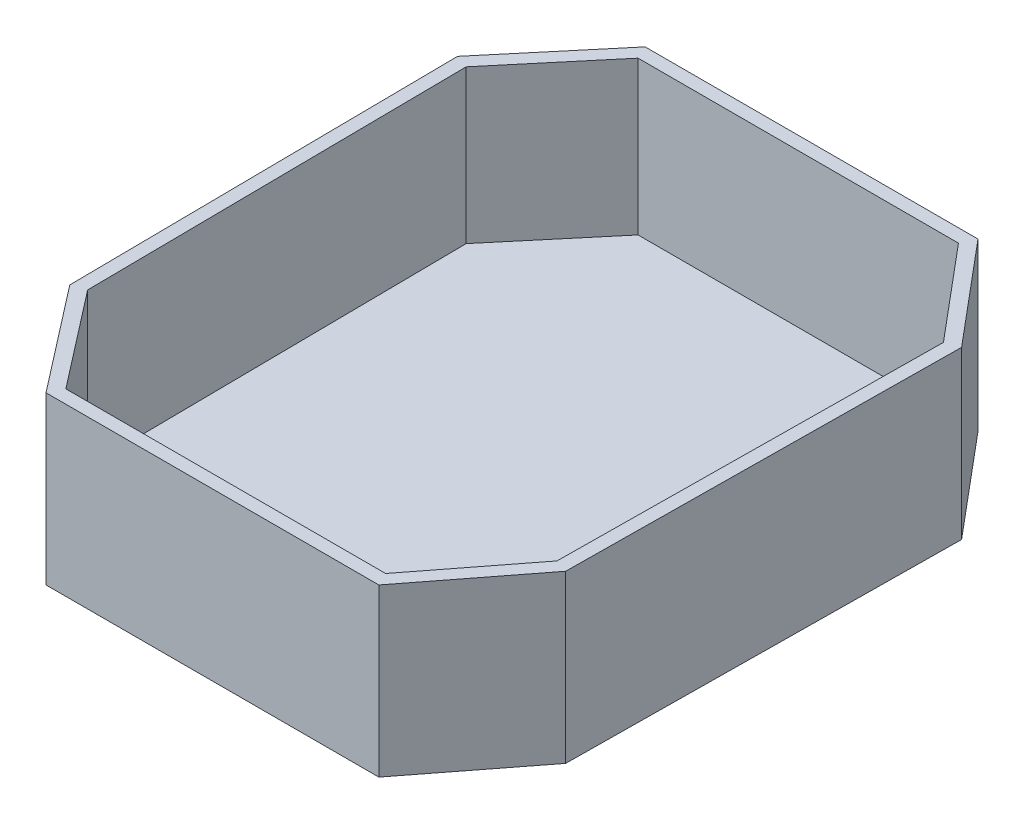
SolidWorks part; units mm, degrees
ref_plane "Ebene vorne" through (0, 0, 0) normal (0, 0, 1) x (1, 0, 0)
ref_plane "Ebene oben" through (0, 0, 0) normal (0, 1, 0) x (1, 0, 0)
ref_plane "Ebene rechts" through (0, 0, 0) normal (1, 0, 0) x (0, 0, -1)
sketch "Skizze1" plane through (0, 0, 0) normal (0, 1, 0) x (1, 0, 0)
  line L0 (-71.7828, 0) -> (65.2574, 0) construction
  line L1 (-55, 0) -> (55, 0) construction
  line L2 (0, 50.8602) -> (0, -44.8504) construction
  line L3 (0, -55) -> (0, 55) construction
  line L4 (0, -50.1714) -> (-25, -50.1714)
  line L5 (-25, -50.1714) -> (-37.2443, -34.3575)
  line L6 (-37.2443, -34.3575) -> (-37.8558, 24.5078)
  line L7 (-37.8558, 24.5078) -> (-25, 39.8286)
  line L8 (-25, 39.8286) -> (0, 39.8286)
  line L9 (0, 39.8286) -> (0, -50.1714)
  dimension "D1" = 25
  dimension "D2" = 130
  dimension "D3" = 20
  dimension "D4" = 90
extrude "Aufsatz-Linear austragen1" add sketch "Skizze1" along normal blind 25
mirror "Spiegeln1" about plane through (0, 0, 0) normal (1, 0, 0) of "Aufsatz-Linear austragen1"
shell "Wandung2" thickness 2
